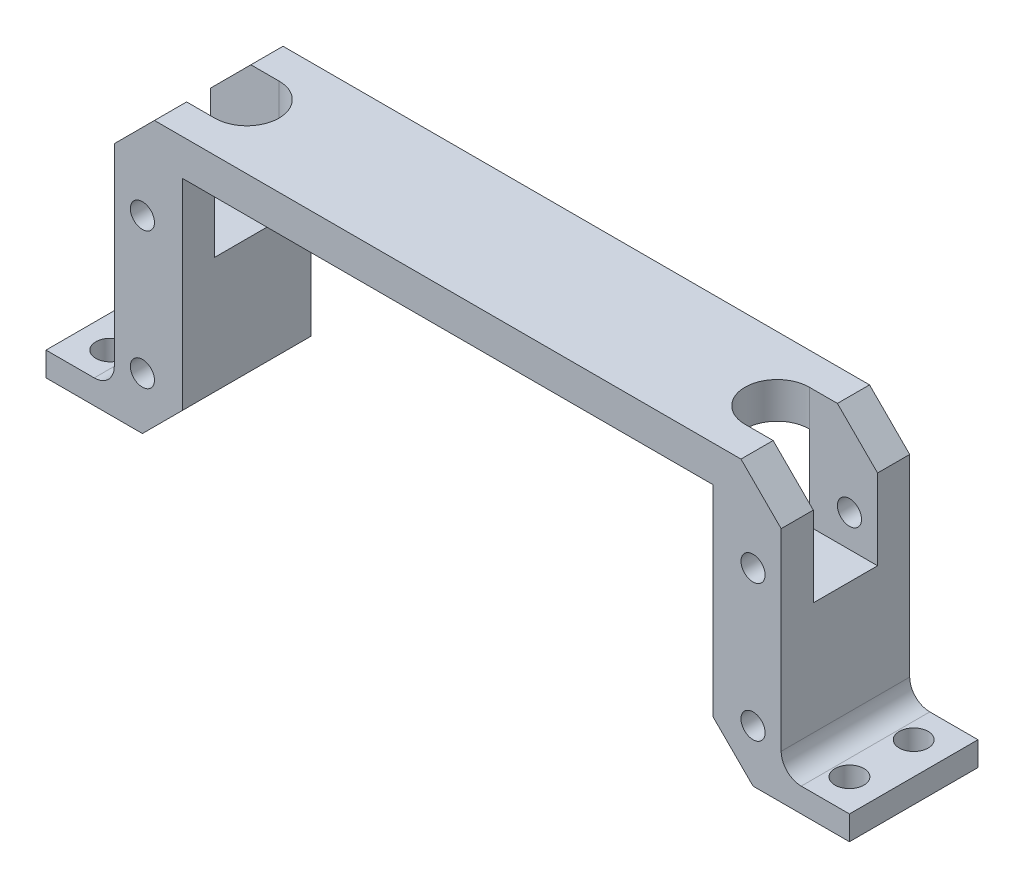
SolidWorks part; units mm, degrees
other "Markup1"
sketch "Sketch6" plane through (-36, 25, 8) normal (-0.8707, 0.2235, 0.4381) x (0.4473, -0.0107, 0.8943)
material "Nylon PA 12"
ref_plane "Front Plane" through (0, 0, 0) normal (0, 0, 1) x (1, 0, 0)
ref_plane "Top Plane" through (0, 0, 0) normal (0, 1, 0) x (1, 0, 0)
ref_plane "Right Plane" through (0, 0, 0) normal (1, 0, 0) x (0, 0, -1)
sketch "Sketch1" plane through (0, 0, 0) normal (0, 0, 1) x (1, 0, 0)
  line L0 (-50, 0) -> (-33, 0)
  line L1 (-33, 0) -> (-33, 30)
  line L2 (-33, 30) -> (33, 30)
  line L3 (33, 30) -> (33, 0)
  line L4 (33, 0) -> (50, 0)
  line L5 (-50, 0) -> (-50, 3)
  line L6 (-50, 3) -> (-41.5, 3)
  line L7 (50, 0) -> (50, 3)
  line L8 (50, 3) -> (41.5, 3)
  line L9 (-41.5, 3) -> (-41.5, 34.5)
  line L10 (-41.5, 34.5) -> (41.5, 34.5)
  line L11 (41.5, 34.5) -> (41.5, 3)
  dimension "D1" = 100
  dimension "D2" = 17
  dimension "D3" = 66
  dimension "D4" = 33
  dimension "D5" = 30
  dimension "D6" = 3
  dimension "D7" = 17
  dimension "D8" = 4.5
  dimension "D9" = 8.5
  dimension "D10" = 8.5
extrude "Boss-Extrude1" add sketch "Sketch1" along normal mid plane 16
chamfer "Chamfer5" distance 5 angle 45 4 edges at (-41.5, 34.5, 0) (33, 0, 0) (-33, 0, 0) (41.5, 34.5, 0)
fillet "Fillet1" radius 2.5 2 edges at (41.5, 3, 0) (-41.5, 3, 0)
sketch "Sketch2" plane through (0, 0, 8) normal (0, 0, 1) x (1, 0, 0)
  line L2 (38, 37.1974) -> (38, -3.6862) construction
  circle A2 centre (38, 23.5) radius 1.5
  circle A3 centre (38, 6.5) radius 1.5
  dimension "D1" = 38
  dimension "D2" = 6.5
  dimension "D3" = 17
extrude "Cut-Extrude1" cut sketch "Sketch2" against normal through all
mirror "Mirror1" about plane through (0, 0, 0) normal (1, 0, 0) of "Cut-Extrude1"
sketch "Sketch3" plane through (0, 3, 0) normal (0, 1, 0) x (1, 0, 0)
  line L0 (50, -8) -> (50, 8) construction
  line L1 (44, 28.8859) -> (44, -25.0715) construction
  line L2 (-44, 27.8941) -> (-44, -24.0796) construction
  line L3 (-44, -8) -> (-44, 8) construction
  line L4 (44, 8) -> (44, -8) construction
  line L5 (56.6832, -8) -> (-41.1826, -8) construction
  line L6 (65.7079, 8) -> (-46.658, 8) construction
  line L7 (50, 8) -> (44, 8) construction
  line L8 (50, -8) -> (44, -8) construction
  line L9 (50, 29.9064) -> (50, -19.7738) construction
  circle A0 centre (46, 4) radius 1.8
  circle A1 centre (46, -4) radius 1.8
  circle A2 centre (-46, 4) radius 1.8
  circle A3 centre (-46, -4) radius 1.8
  dimension "D2" = 3.6
  dimension "D3" = 3.6
  dimension "D12" = 3.6
  dimension "D14" = 3.6
  dimension "D1" = 2
  dimension "D4" = 16
  dimension "D5" = 4
  dimension "D6" = 4
  dimension "D7" = 6
  dimension "D8" = 2
  dimension "D9" = 4
  dimension "D10" = 12
  dimension "D11" = 16
  dimension "D13" = 4
  dimension "D15" = 88
extrude "Cut-Extrude2" cut sketch "Sketch3" against normal through all
sketch "Sketch5" plane through (0, 34.5, 0) normal (0, 1, 0) x (1, 0, 0)
  line L0 (-41.5, -8) -> (-41.5, 8) construction
  line L6 (-46, 4) -> (-41.5, 4) construction
  line L7 (46, 4) -> (46, -4) construction
  line L8 (46, -4) -> (41.5, -4) construction
  line L9 (-46, -4) -> (-46, 4) construction
  line L13 (41.5, 8) -> (41.5, -8) construction
  line L18 (-41.5, -4) -> (-46, -4) construction
  line L21 (41.5, 4) -> (46, 4) construction
  line L32 (33, -8) -> (33, 8) construction
  line L33 (41.5, 4) -> (33, 4)
  line L34 (41.5, 4) -> (41.5, -4)
  line L35 (41.5, -4) -> (33, -4)
  line L36 (33, 4) -> (33, -4)
  line L37 (-33, -8) -> (-33, 8) construction
  line L38 (-41.5, 4) -> (-33, 4)
  line L39 (-41.5, 4) -> (-41.5, -4)
  line L40 (-41.5, -4) -> (-33, -4)
  line L41 (-33, 4) -> (-33, -4)
extrude "Cut-Extrude3" cut sketch "Sketch5" against normal blind 15
sketch "Sketch7" plane through (0, 34.5, 0) normal (0, 1, 0) x (1, 0, 0)
  line L0 (-36.5, 4) -> (-36.5, -4) construction
  line L1 (-33, -4) -> (-33, 4) construction
  line L2 (33, 4) -> (33, -4) construction
  line L3 (33, 4) -> (33, -4)
  line L4 (-33, 4) -> (-33, -4)
  arc A0 (-33, -4) -> (-33, 4) centre (-33, 0) ccw
  arc A1 (33, 4) -> (33, -4) centre (33, 0) ccw
extrude "Cut-Extrude5" cut sketch "Sketch7" against normal blind 15
